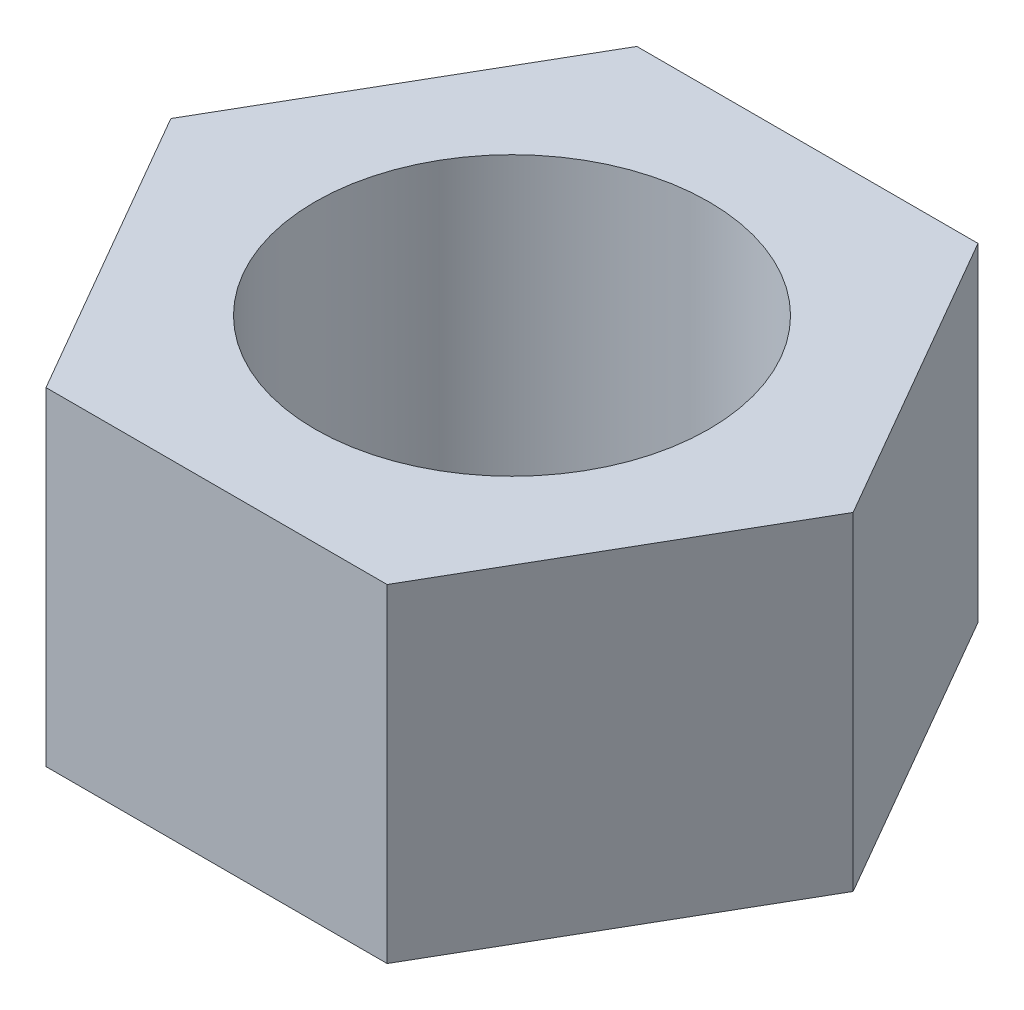
SolidWorks part; units mm, degrees
ref_plane "Front Plane" through (0, 0, 0) normal (0, 0, 1) x (1, 0, 0)
ref_plane "Top Plane" through (0, 0, 0) normal (0, 1, 0) x (1, 0, 0)
ref_plane "Right Plane" through (0, 0, 0) normal (1, 0, 0) x (0, 0, -1)
sketch "Sketch1" plane through (0, 0, 0) normal (0, 1, 0) x (1, 0, 0)
  line L1 (1.299, -2.25) -> (2.5981, 0)
  line L2 (2.5981, 0) -> (1.299, 2.25)
  line L3 (1.299, 2.25) -> (-1.299, 2.25)
  line L4 (-1.299, 2.25) -> (-2.5981, 0)
  line L5 (-2.5981, 0) -> (-1.299, -2.25)
  line L6 (-1.299, -2.25) -> (1.299, -2.25)
  circle A0 centre (0, 0) radius 2.25 construction
  dimension "D1" = 4.5
extrude "Boss-Extrude1" add sketch "Sketch1" along normal blind 2.5
sketch "Sketch2" plane through (0, 2.5, 0) normal (0, 1, 0) x (1, 0, 0)
  circle A0 centre (0, 0) radius 1.5
extrude "Cut-Extrude1" cut sketch "Sketch2" against normal blind 2.5
